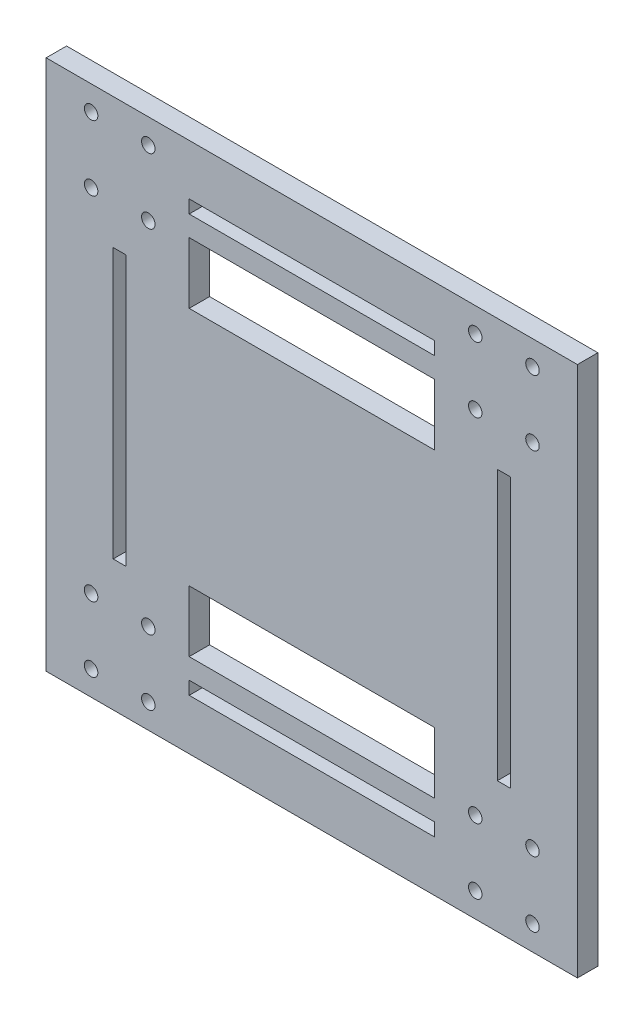
SolidWorks part; units mm, degrees
ref_plane "前视基准面" through (0, 0, 0) normal (0, 0, 1) x (1, 0, 0)
ref_plane "上视基准面" through (0, 0, 0) normal (0, 1, 0) x (1, 0, 0)
ref_plane "右视基准面" through (0, 0, 0) normal (1, 0, 0) x (0, 0, -1)
sketch "草图1" plane through (0, 0, 0) normal (0, 0, 1) x (1, 0, 0)
  line L1 (-65, 65) -> (65, 65)
  line L2 (-65, 65) -> (-65, -65)
  line L3 (-65, -65) -> (65, -65)
  line L4 (65, 65) -> (65, -65)
  line L5 (-65, 65) -> (65, -65) construction
  line L6 (-65, -65) -> (65, 65) construction
  point P0 (0, 0)
  dimension "D1" = 130
  dimension "D2" = 130
extrude "凸台-拉伸1" add sketch "草图1" along normal blind 5
sketch "草图2" plane through (0, 0, 5) normal (0, 0, 1) x (1, 0, 0)
  line L0 (-65, 65) -> (-65, -65) construction
  line L1 (65, 65) -> (-65, 65) construction
  line L2 (65, -65) -> (65, 65) construction
  line L3 (-65, -65) -> (65, -65) construction
  circle A0 centre (-54, 59) radius 1.65
  circle A1 centre (-40, 59) radius 1.65
  circle A2 centre (-40, 43) radius 1.65
  circle A3 centre (-54, 43) radius 1.65
  circle A4 centre (40, 59) radius 1.65
  circle A5 centre (54, 59) radius 1.65
  circle A6 centre (54, 43) radius 1.65
  circle A7 centre (40, 43) radius 1.65
  circle A8 centre (40, -43) radius 1.65
  circle A9 centre (54, -43) radius 1.65
  circle A10 centre (54, -59) radius 1.65
  circle A11 centre (40, -59) radius 1.65
  circle A12 centre (-54, -43) radius 1.65
  circle A13 centre (-40, -43) radius 1.65
  circle A14 centre (-40, -59) radius 1.65
  circle A15 centre (-54, -59) radius 1.65
  point P10 (0, 0)
  point P11 (0, 0)
  point P12 (0, 0)
  point P23 (0, 0)
  dimension "D1" = 3.3
  dimension "D2" = 3.3
  dimension "D3" = 3.3
  dimension "D4" = 3.3
  dimension "D5" = 14
  dimension "D6" = 14
  dimension "D7" = 16
  dimension "D8" = 11
  dimension "D9" = 6
  dimension "D10" = 11
  dimension "D11" = 14
  dimension "D12" = 16
  dimension "D13" = 11
  dimension "D14" = 6
  dimension "D15" = 14
  dimension "D16" = 16
  dimension "D17" = 6
  dimension "D18" = 11
  dimension "D19" = 14
  dimension "D20" = 16
  dimension "D21" = 6
  dimension "D22" = 11
extrude "切除-拉伸1" cut sketch "草图2" against normal blind 5
sketch "草图3" plane through (0, 0, 5) normal (0, 0, 1) x (1, 0, 0)
  line L0 (54, 43) -> (40, 43) construction
  line L1 (47, 43) -> (47, -43) construction
  line L2 (54, -43) -> (40, -43) construction
  line L3 (0, 67.7305) -> (0, -73.1489) construction
  line L4 (48.6, 33) -> (45.4, 33)
  line L5 (48.6, 33) -> (48.6, -33)
  line L6 (48.6, -33) -> (45.4, -33)
  line L7 (45.4, 33) -> (45.4, -33)
  line L8 (48.6, 33) -> (45.4, -33) construction
  line L9 (48.6, -33) -> (45.4, 33) construction
  line L10 (-48.6, -33) -> (-45.4, -33)
  line L11 (-48.6, 33) -> (-48.6, -33)
  line L12 (-48.6, 33) -> (-45.4, 33)
  line L13 (-45.4, 33) -> (-45.4, -33)
  line L14 (-40, -43) -> (-40, -59) construction
  line L15 (-40, -51) -> (40, -51) construction
  line L16 (28.1409, 0) -> (-28.6653, 0) construction
  line L17 (30, -49.4) -> (-30, -49.4)
  line L18 (30, -49.4) -> (30, -52.6)
  line L19 (30, -52.6) -> (-30, -52.6)
  line L20 (-30, -49.4) -> (-30, -52.6)
  line L21 (30, -49.4) -> (-30, -52.6) construction
  line L22 (30, -52.6) -> (-30, -49.4) construction
  line L23 (-30, 49.4) -> (-30, 52.6)
  line L24 (30, 52.6) -> (-30, 52.6)
  line L25 (30, 49.4) -> (30, 52.6)
  line L26 (30, 49.4) -> (-30, 49.4)
  point P10 (47, 0)
  point P28 (0, -51)
  dimension "D1" = 3.2
  dimension "D2" = 66
  dimension "D3" = 3.2
  dimension "D4" = 60
extrude "切除-拉伸2" cut sketch "草图3" against normal blind 10
sketch "草图4" plane through (0, 0, 0) normal (0, 0, -1) x (-1, 0, 0)
  line L0 (30, 49.4) -> (-30, 49.4) construction
  line L1 (-30, 44.4) -> (30, 44.4)
  line L2 (-30, 44.4) -> (-30, 29.4)
  line L3 (-30, 29.4) -> (30, 29.4)
  line L4 (30, 44.4) -> (30, 29.4)
  line L5 (-30, 44.4) -> (30, 29.4) construction
  line L6 (-30, 29.4) -> (30, 44.4) construction
  line L7 (-33.035, 0) -> (35.1325, 0) construction
  line L8 (-30, -29.4) -> (30, -29.4)
  line L9 (30, -44.4) -> (30, -29.4)
  line L10 (-30, -44.4) -> (30, -44.4)
  line L11 (-30, -44.4) -> (-30, -29.4)
  point P0 (0, 36.9)
  dimension "D1" = 15
  dimension "D2" = 5
  dimension "D3" = 60
extrude "切除-拉伸3" cut sketch "草图4" against normal blind 10
ref_plane "基准面1" through (48.6, 33, 0) normal (0, 1, 0) x (1, 0, 0)
